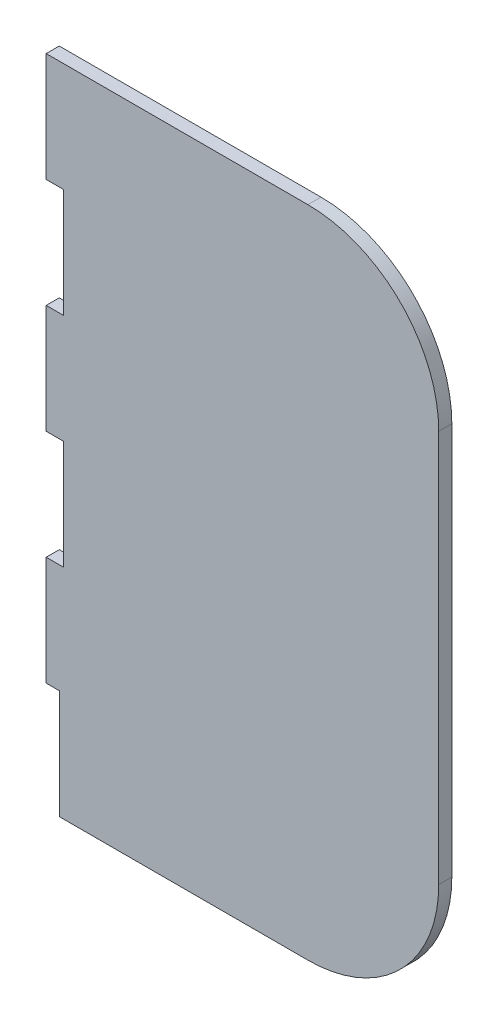
SolidWorks part; units mm, degrees
ref_plane "Plan de face" through (0, 0, 0) normal (0, 0, 1) x (1, 0, 0)
ref_plane "Plan de dessus" through (0, 0, 0) normal (0, 1, 0) x (1, 0, 0)
ref_plane "Plan de droite" through (0, 0, 0) normal (1, 0, 0) x (0, 0, -1)
sketch "Esquisse1" plane through (0, 0, 0) normal (0, 0, 1) x (1, 0, 0)
  line L1 (0, 0) -> (90, 0)
  line L2 (0, 0) -> (0, 150)
  line L3 (0, 150) -> (90, 150)
  line L4 (90, 0) -> (90, 150)
  dimension "D1" = 150
  dimension "D2" = 90
extrude "Boss.-Extru.2" add sketch "Esquisse1" along normal blind 3 contours L3 L4 L1 L2
sketch "Esquisse3" plane through (0, 0, 3) normal (0, 0, 1) x (1, 0, 0)
  line L0 (0, 0) -> (0, 150) construction
  line L1 (0, 125) -> (3.9352, 125)
  line L2 (0, 125) -> (0, 100)
  line L3 (0, 100) -> (3.9352, 100)
  line L4 (3.9352, 125) -> (3.9352, 100)
  line L5 (0, 150) -> (90, 150) construction
  line L6 (0, 75) -> (3.9352, 75)
  line L7 (0, 75) -> (0, 50)
  line L8 (0, 50) -> (3.9352, 50)
  line L9 (3.9352, 75) -> (3.9352, 50)
  line L11 (0, 0) -> (3, 0)
  line L12 (0, 0) -> (0, 25)
  line L13 (0, 25) -> (3, 25)
  line L14 (3, 0) -> (3, 25)
  dimension "D1" = 25
  dimension "D2" = 25
  dimension "D3" = 25
  dimension "D4" = 25
  dimension "D5" = 3
  dimension "D6" = 25
extrude "Enlèv. mat.-Extru.1" cut sketch "Esquisse3" against normal blind 3
fillet "Congé1" radius 30 2 edges at (90, 0, 1.5) (90, 150, 1.5)
